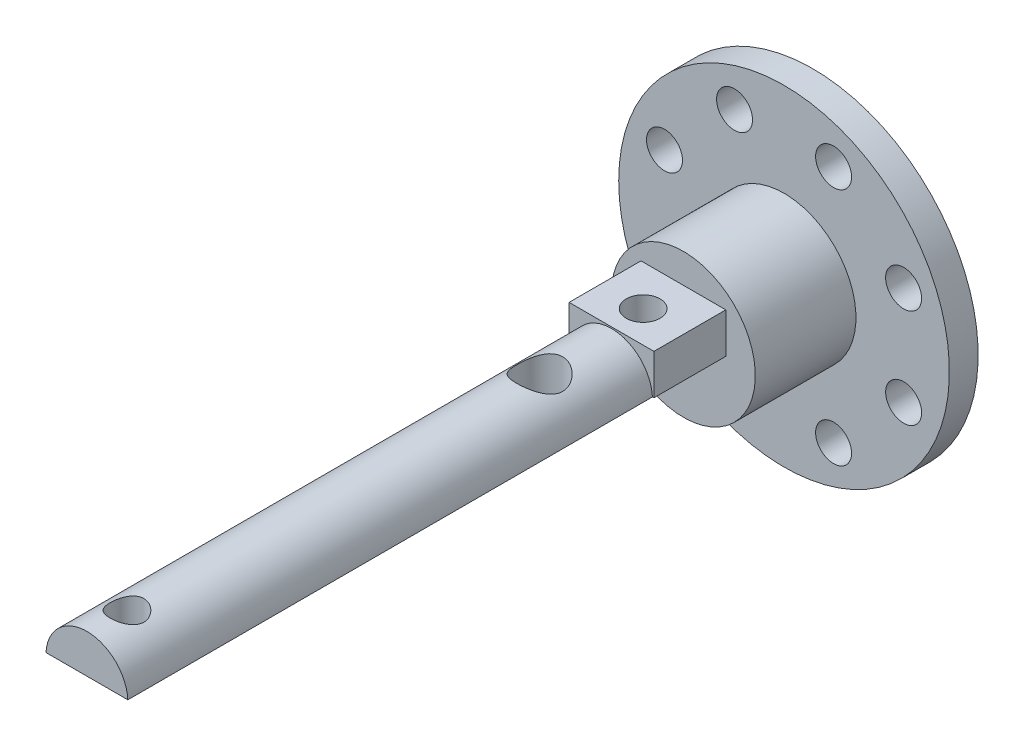
SolidWorks part; units mm, degrees
ref_plane "정면" through (0, 0, 0) normal (0, 0, 1) x (1, 0, 0)
ref_plane "윗면" through (0, 0, 0) normal (0, 1, 0) x (1, 0, 0)
ref_plane "우측면" through (0, 0, 0) normal (1, 0, 0) x (0, 0, -1)
sketch "스케치1" plane through (0, 0, 0) normal (0, 0, 1) x (1, 0, 0)
  circle A0 centre (0, 0) radius 2.85
  dimension "D1" = 5.7
extrude "보스-돌출1" add sketch "스케치1" along normal blind 31.5 contours A0
sketch "스케치3" plane through (0, 0, 0) normal (0, 0, -1) x (-1, 0, 0)
  line L1 (2.95, -2.95) -> (-2.95, -2.95)
  line L2 (2.95, -2.95) -> (2.95, 2.95)
  line L3 (2.95, 2.95) -> (-2.95, 2.95)
  line L4 (-2.95, -2.95) -> (-2.95, 2.95)
  line L5 (2.95, -2.95) -> (-2.95, 2.95) construction
  line L6 (2.95, 2.95) -> (-2.95, -2.95) construction
  point P0 (0, 0)
  dimension "D1" = 5.9
  dimension "D2" = 5.9
extrude "보스-돌출2" add sketch "스케치3" along normal blind 5
sketch "스케치4" plane through (0, 0, -5) normal (0, 0, -1) x (-1, 0, 0)
  circle A0 centre (0, 0) radius 5
  dimension "D1" = 10
extrude "보스-돌출3" add sketch "스케치4" along normal blind 7
sketch "스케치6" plane through (0, 0, -12) normal (0, 0, -1) x (-1, 0, 0)
  circle A0 centre (0, 0) radius 11.5
  dimension "D1" = 23
extrude "보스-돌출4" add sketch "스케치6" along normal blind 2
sketch "스케치8" plane through (0, 0, -14) normal (0, 0, -1) x (-1, 0, 0)
  circle A0 centre (0, 0) radius 4.5
  dimension "D1" = 9
extrude "컷-돌출2" cut sketch "스케치8" against normal blind 7.5
sketch "스케치9" plane through (0, 0, -14) normal (0, 0, -1) x (-1, 0, 0)
  line L0 (0, 0) -> (0, 14.2749) construction
  line L1 (0, 0) -> (-5.348, 12.9112) construction
  circle A0 centre (3.4442, 8.3149) radius 1.25
  circle A1 centre (-3.4442, 8.3149) radius 1.25
  circle A2 centre (8.3149, 3.4442) radius 1.25
  circle A3 centre (8.3149, -3.4442) radius 1.25
  circle A4 centre (3.4442, -8.3149) radius 1.25
  circle A5 centre (-3.4442, -8.3149) radius 1.25
  circle A6 centre (-8.3149, -3.4442) radius 1.25
  circle A7 centre (-8.3149, 3.4442) radius 1.25
  point P24 (0, 0)
  dimension "D2" = 8
  dimension "D4" = 2.5
  dimension "D1" = 22.5
  dimension "D3" = 9
extrude "컷-돌출3" cut sketch "스케치9" against normal blind 5.5
sketch "스케치10" plane through (0, 2.95, 0) normal (0, 1, 0) x (1, 0, 0)
  circle A0 centre (0, 2.2) radius 1.175
  dimension "D2" = 2.35
  dimension "D1" = 2.2
extrude "컷-돌출7" cut sketch "스케치10" against normal blind 10
sketch "스케치11" plane through (0, 2.95, 0) normal (0, 1, 0) x (1, 0, 0)
  line L2 (-2.95, 5) -> (-2.95, 0) construction
  line L4 (-2.95, 2.6468) -> (2.95, 2.6468) construction
  line L5 (2.95, 5) -> (2.95, 0) construction
sketch "스케치12" plane through (0, 0, 31.5) normal (0, 0, 1) x (1, 0, 0)
  line L0 (-2.95, 2.95) -> (2.95, 2.95) construction
  line L1 (2.95, -2.95) -> (-2.95, -2.95)
  line L2 (2.95, -2.95) -> (2.95, 2.95)
  line L3 (2.95, 2.95) -> (-2.95, 2.95)
  line L4 (-2.95, -2.95) -> (-2.95, 2.95)
  line L5 (2.95, -2.95) -> (-2.95, 2.95) construction
  line L6 (2.95, 2.95) -> (-2.95, -2.95) construction
  line L7 (-2.95, -2.95) -> (-2.95, 2.95) construction
  point P0 (0, 0)
extrude "보스-돌출5" add sketch "스케치12" along normal blind 45
sketch "스케치15" plane through (0, 0, 76.5) normal (0, 0, 1) x (1, 0, 0)
  line L1 (2.95, -10.0246) -> (-2.95, -10.0246)
  line L2 (2.95, -10.0246) -> (2.95, 10.0246)
  line L3 (2.95, 10.0246) -> (-2.95, 10.0246)
  line L4 (-2.95, -10.0246) -> (-2.95, 10.0246)
  line L5 (2.95, -10.0246) -> (-2.95, 10.0246) construction
  line L6 (2.95, 10.0246) -> (-2.95, -10.0246) construction
  point P0 (0, 0)
  dimension "D1" = 5.9
extrude "보스-돌출6" add sketch "스케치15" along normal blind 6
sketch "스케치7" plane through (0, 0, -14) normal (0, 0, -1) x (-1, 0, 0)
  circle A0 centre (0, 12) radius 1.05
  dimension "D1" = 2.1
  dimension "D2" = 12
sketch "스케치16" plane through (0, 2.95, 0) normal (0, 1, 0) x (1, 0, 0)
  line L0 (2.95, -31.5) -> (-2.95, -31.5) construction
  circle A0 centre (0, -33.7) radius 1.175
  dimension "D2" = 2.35
  dimension "D1" = 2.2
extrude "컷-돌출8" cut sketch "스케치16" against normal blind 10
sketch "스케치18" plane through (2.95, 0, 0) normal (1, 0, 0) x (0, 0, -1)
  line L0 (-76.5, -2.95) -> (-31.5, -2.95) construction
  line L1 (-36.5, -2.95) -> (5, -2.95)
  line L2 (-36.5, -2.95) -> (-36.5, 0.15)
  line L3 (-36.5, 0.15) -> (5, 0.15)
  line L4 (5, -2.95) -> (5, 0.15)
  line L5 (5, 5) -> (5, -5) construction
  dimension "D1" = 3.1
  dimension "D2" = 41.5
extrude "컷-돌출9" cut sketch "스케치18" against normal blind 10
sketch "스케치19" plane through (2.95, 0, 0) normal (1, 0, 0) x (0, 0, -1)
  line L1 (-82.5, 10.0246) -> (-36.4834, 10.0246)
  line L2 (-82.5, 10.0246) -> (-82.5, -16.8998)
  line L3 (-82.5, -16.8998) -> (-36.4834, -16.8998)
  line L4 (-36.4834, 10.0246) -> (-36.4834, -16.8998)
extrude "컷-돌출10" cut sketch "스케치19" against normal blind 10
sketch "스케치21" plane through (0, 0, 36.4834) normal (0, 0, 1) x (1, 0, 0)
  circle A0 centre (0, 0) radius 2.85
  dimension "D1" = 5.7
extrude "컷-돌출11" cut sketch "스케치21" against normal blind 10 flip side to cut contours A0
sketch "스케치22" plane through (0, 2.95, 0) normal (0, 1, 0) x (1, 0, 0)
  circle A0 centre (0, -5) radius 1.6
  dimension "D2" = 3.2
  dimension "D1" = 5
extrude "컷-돌출12" cut sketch "스케치22" against normal blind 3
